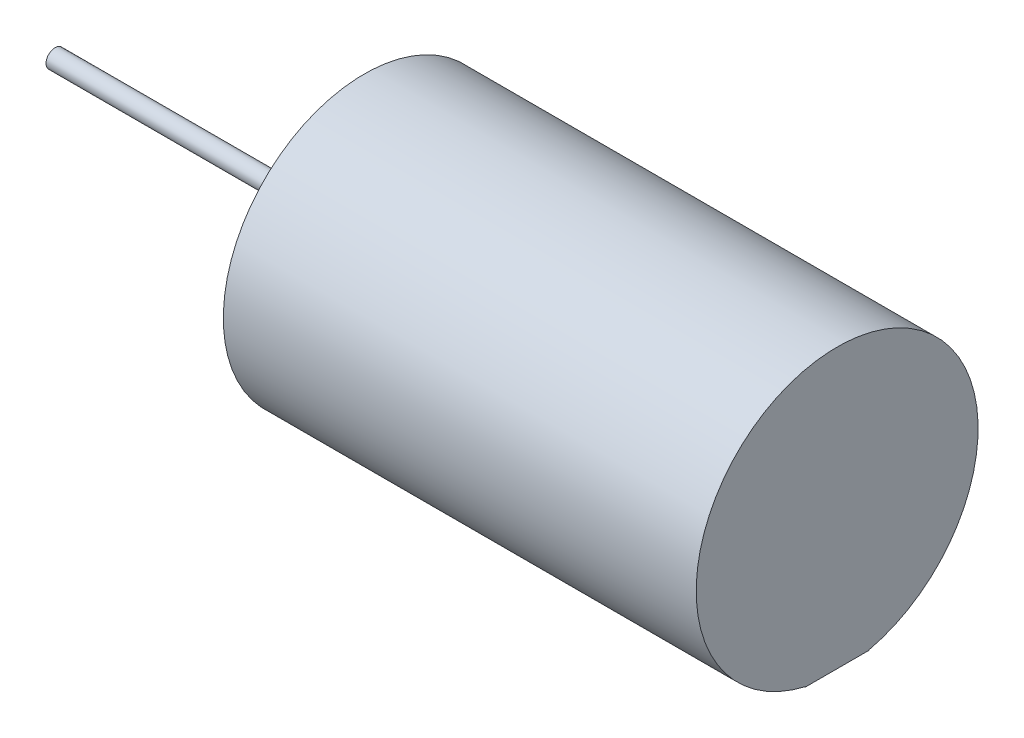
SolidWorks part; units mm, degrees
ref_plane "Front Plane" through (0, 0, 0) normal (0, 0, 1) x (1, 0, 0)
ref_plane "Top Plane" through (0, 0, 0) normal (0, 1, 0) x (1, 0, 0)
ref_plane "Right Plane" through (0, 0, 0) normal (1, 0, 0) x (0, 0, -1)
sketch "Sketch1" plane through (0, 0, 0) normal (0, 1, 0) x (1, 0, 0)
  line L1 (-26, 20) -> (26, 20)
  line L2 (-26, 20) -> (-26, -20)
  line L3 (-26, -20) -> (26, -20)
  line L4 (26, 20) -> (26, -20)
  line L5 (0, -20) -> (0, 20) construction
  line L6 (-26, 0) -> (26, 0) construction
  point P0 (0, 0)
  dimension "D1" = 52
  dimension "D2" = 40
extrude "Boss-Extrude1" add sketch "Sketch1" along normal blind 3
sketch "Sketch2" plane through (0, 3, 0) normal (0, 1, 0) x (1, 0, 0)
  line L0 (0, 0) -> (-26, 0) construction
  line L1 (-26, 20) -> (-26, -20) construction
  line L2 (-16, 3.5) -> (-16, -3.5)
  line L3 (-16, 3.5) -> (19, 3.5)
  line L4 (19, 3.5) -> (19, -3.5)
  line L5 (19, -3.5) -> (-16, -3.5)
  dimension "D1" = 7
  dimension "D2" = 3.5
  dimension "D3" = 10
  dimension "D4" = 35
extrude "Boss-Extrude2" add sketch "Sketch2" along normal blind 40
sketch "Sketch3" plane through (0, 0, -3.5) normal (0, 0, -1) x (-1, 0, 0)
  line L0 (-19, 3) -> (-19, 43) construction
  line L1 (-19, 43) -> (1, 43) construction
  line L2 (-19, 43) -> (16, 43) construction
  line L3 (1, 43) -> (16, 3)
  line L4 (16, 3) -> (-19, 3) construction
  line L5 (1, 43) -> (16, 43)
  line L6 (16, 43) -> (16, 3)
  dimension "D1" = 20
extrude "Cut-Extrude1" cut sketch "Sketch3" against normal through all
sketch "Sketch4" plane through (0, 43, 0) normal (0, 1, 0) x (1, 0, 0)
  line L1 (26, -20) -> (-26, -20)
  line L2 (26, -20) -> (26, 20)
  line L3 (26, 20) -> (-26, 20)
  line L4 (-26, -20) -> (-26, 20)
  line L5 (0, 20) -> (0, -20) construction
  line L6 (26, 0) -> (-26, 0) construction
  point P0 (0, 0)
  dimension "D1" = 52
  dimension "D2" = 40
extrude "Boss-Extrude3" add sketch "Sketch4" along normal blind 31
sketch "Sketch5" plane through (-26, 0, 0) normal (-1, 0, 0) x (0, 0, 1)
  line L0 (0, 74) -> (0, 43) construction
  line L1 (-20, 74) -> (20, 74) construction
  line L2 (-20, 43) -> (20, 43) construction
  line L3 (20, 58.5) -> (-20, 58.5) construction
  line L4 (20, 74) -> (20, 43) construction
  line L5 (-20, 74) -> (-20, 43) construction
  line L8 (-20, 43) -> (-20, 74)
  line L9 (-20, 74) -> (0, 74)
  line L10 (-20, 43) -> (-3.5, 43)
  line L13 (-3.5, 43) -> (-3.5, 43.4003)
  arc A0 (0, 74) -> (-3.5, 43.4003) centre (0, 58.5) ccw
  dimension "D1" = 3.5
extrude "Cut-Extrude10" cut sketch "Sketch5" against normal through all
sketch "Sketch7" plane through (-26, 0, 0) normal (-1, 0, 0) x (0, 0, 1)
  line L0 (0, 74) -> (20, 74)
  line L1 (20, 74) -> (20, 43)
  line L2 (3.5, 43) -> (20, 43)
  line L3 (-3.5, 43) -> (20, 43) construction
  line L4 (3.5, 43) -> (3.5, 43.4003)
  arc A0 (3.5, 43.4003) -> (0, 74) centre (0, 58.5) ccw
extrude "Cut-Extrude11" cut sketch "Sketch7" against normal through all
sketch "Sketch8" plane through (-26, 0, 0) normal (-1, 0, 0) x (0, 0, 1)
  circle A0 centre (0, 58.5) radius 5
  dimension "D1" = 10
extrude "Boss-Extrude4" add sketch "Sketch8" along normal blind 3
sketch "Sketch9" plane through (-29, 0, 0) normal (-1, 0, 0) x (0, 0, 1)
  circle A0 centre (0, 58.5) radius 1
  dimension "D1" = 2
extrude "Boss-Extrude5" add sketch "Sketch9" along normal blind 31
ref_plane "Plane1" through (30, 0, 0) normal (-1, 0, 0) x (0, 0, 1)
sketch "Sketch10" plane through (30, 0, 0) normal (-1, 0, 0) x (0, 0, 1)
  line L1 (21.1836, -0.8188) -> (-22.0282, -0.8188)
  line L2 (21.1836, -0.8188) -> (21.1836, 43.3554)
  line L3 (21.1836, 43.3554) -> (-22.0282, 43.3554)
  line L4 (-22.0282, -0.8188) -> (-22.0282, 43.3554)
extrude "Cut-Extrude12" cut sketch "Sketch10" along normal blind 70
